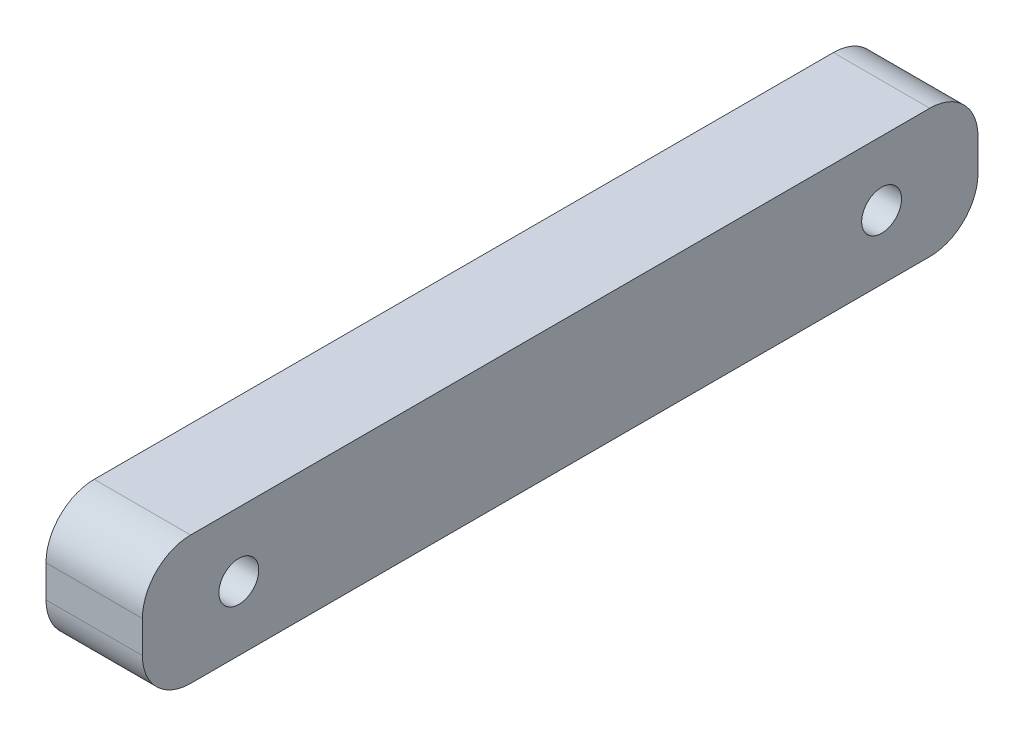
SolidWorks part; units mm, degrees
other "Markup1"
sketch "Sketch3" plane through (12.7, -22.225, -203.2) normal (1, 0, 0) x (0, 0, -1)
sketch "Sketch4" plane through (12.7, -22.225, -203.2) normal (1, 0, 0) x (0, 0, -1)
sketch "Sketch5" plane through (25.4, -22.225, -203.2) normal (1, 0, 0) x (0, 0, -1)
sketch "Sketch6" plane through (19.05, -25.4, -165.1) normal (1, 0, 0) x (0, 0, -1)
material "PE High Density"
ref_plane "Front Plane" through (0, 0, 0) normal (0, 0, 1) x (1, 0, 0)
ref_plane "Top Plane" through (0, 0, 0) normal (0, 1, 0) x (1, 0, 0)
ref_plane "Right Plane" through (0, 0, 0) normal (1, 0, 0) x (0, 0, -1)
sketch "Sketch1" plane through (0, 0, 0) normal (1, 0, 0) x (0, 0, -1)
  line L9 (9.525, 0) -> (155.575, 0)
  line L26 (0, -9.525) -> (0, -15.875)
  line L27 (9.525, -25.4) -> (155.575, -25.4)
  line L29 (165.1, -9.525) -> (165.1, -15.875)
  circle A2 centre (19.05, -12.7) radius 3.937
  circle A11 centre (146.05, -12.7) radius 3.937
  arc A15 (9.525, 0) -> (0, -9.525) centre (9.525, -9.525) ccw
  arc A23 (0, -15.875) -> (9.525, -25.4) centre (9.525, -15.875) ccw
  arc A24 (155.575, -25.4) -> (165.1, -15.875) centre (155.575, -15.875) ccw
  arc A25 (155.575, 0) -> (165.1, -9.525) centre (155.575, -9.525) cw
  point P40 (0, 0)
  dimension "D7" = 7.874
  dimension "D8" = 9.525
  dimension "D18" = 7.874
  dimension "D4" = 165.1
  dimension "D5" = 9.525
  dimension "D6" = 19.05
  dimension "D2" = 12.7
  dimension "D3" = 25.4
  dimension "D9" = 19.05
  dimension "D11" = 25.4
  dimension "D15" = 12.7
extrude "Boss-Extrude1" add sketch "Sketch1" along normal blind 19.05
